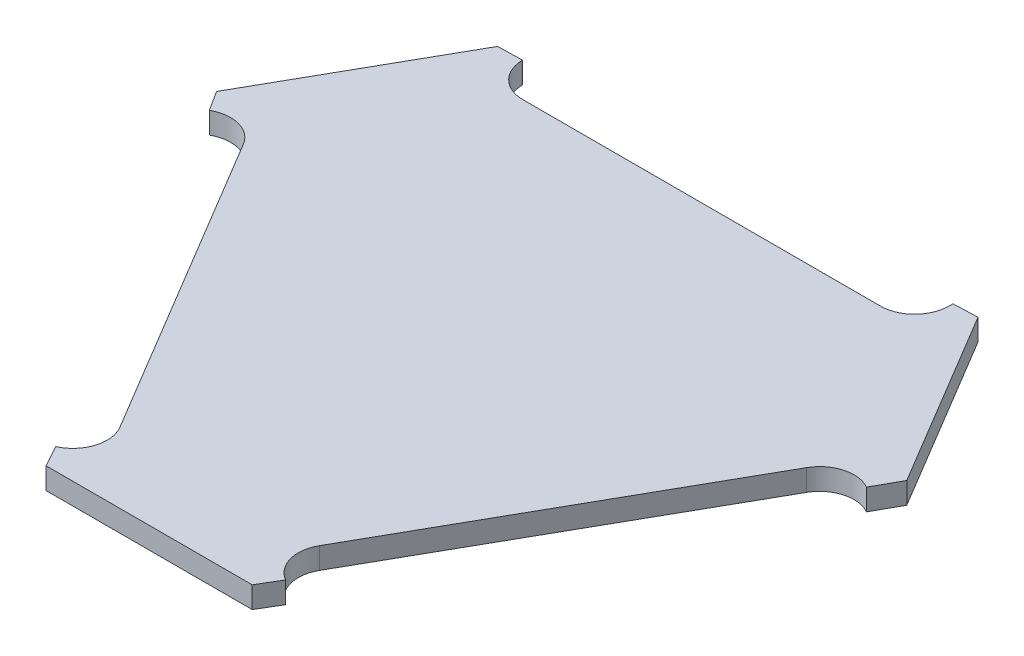
SolidWorks part; units mm, degrees
ref_plane "Plan de face" through (0, 0, 0) normal (0, 0, 1) x (1, 0, 0)
ref_plane "Plan de dessus" through (0, 0, 0) normal (0, 1, 0) x (1, 0, 0)
ref_plane "Plan de droite" through (0, 0, 0) normal (1, 0, 0) x (0, 0, -1)
sketch "Esquisse1" plane through (0, 0, 0) normal (0, 1, 0) x (1, 0, 0)
  line L0 (59.4045, 147.2585) -> (280.5698, 147.2585) construction
  line L1 (112.4267, 8.0585) -> (208.4267, 8.0585)
  line L2 (208.4267, 8.0585) -> (214.2682, 17.8125)
  line L3 (112.4267, 8.0585) -> (106.9536, 18.0238)
  line L4 (156.5271, 235.202) -> (164.3264, 235.202) construction
  line L5 (160.4267, 235.202) -> (160.4267, -84.3922) construction
  line L6 (97.005, 131.4286) -> (101.008, 124.5662) construction
  line L7 (99.0065, 127.9974) -> (397.3645, 302.0396) construction
  line L8 (160.4267, 163.8259) -> (267.3862, 103.1393) construction
  line L9 (224.8872, 131.883) -> (220.9122, 124.8771) construction
  line L10 (48.4635, 282.2813) -> (59.8272, 282.5649)
  line L11 (1.2096, 198.7165) -> (48.4635, 282.2813)
  line L12 (1.2096, 198.7165) -> (7.1198, 189.4008)
  line L13 (318.7618, 202.5231) -> (312.0652, 190.4689)
  line L14 (269.5184, 284.9311) -> (318.7618, 202.5231)
  line L15 (269.5184, 284.9311) -> (258.2593, 284.5177)
  line L16 (59.8272, 282.5649) -> (59.8336, 282.3084)
  line L17 (75.8286, 266.7076) -> (242.2593, 266.7076)
  line L18 (258.2593, 282.7076) -> (258.2593, 284.5177)
  line L19 (28.7166, 183.6729) -> (114.0875, 40.806)
  line L20 (208.3402, 39.5448) -> (290.2621, 184.4171)
  arc A0 (75.8286, 266.7076) -> (59.8336, 282.3084) centre (75.8286, 282.7076) cw
  arc A1 (242.2593, 266.7076) -> (258.2593, 282.7076) centre (242.2593, 282.7076) ccw
  arc A2 (114.0875, 40.806) -> (106.9536, 18.0238) centre (100.3529, 32.5988) cw
  arc A3 (28.7166, 183.6729) -> (7.1198, 189.4008) centre (14.9819, 175.4657) ccw
  arc A4 (290.2621, 184.4171) -> (312.0652, 190.4689) centre (304.1895, 176.5415) cw
  arc A5 (208.3402, 39.5448) -> (214.2682, 17.8125) centre (222.2677, 31.6692) ccw
  point P5 (0, 0)
  point P12 (160.4267, 8.0585)
  point P21 (222.8997, 128.38)
  point P36 (0, 0)
  point P39 (0, 0)
  point P46 (0, 0)
  point P47 (0, 0)
  point P48 (0, 0)
  point P49 (0, 0)
  point P50 (0, 0)
  point P51 (0, 0)
  dimension "D2" = 16
  dimension "D3" = 16
  dimension "D1" = 96
extrude "Boss.-Extru.1" add sketch "Esquisse1" along normal blind 10
